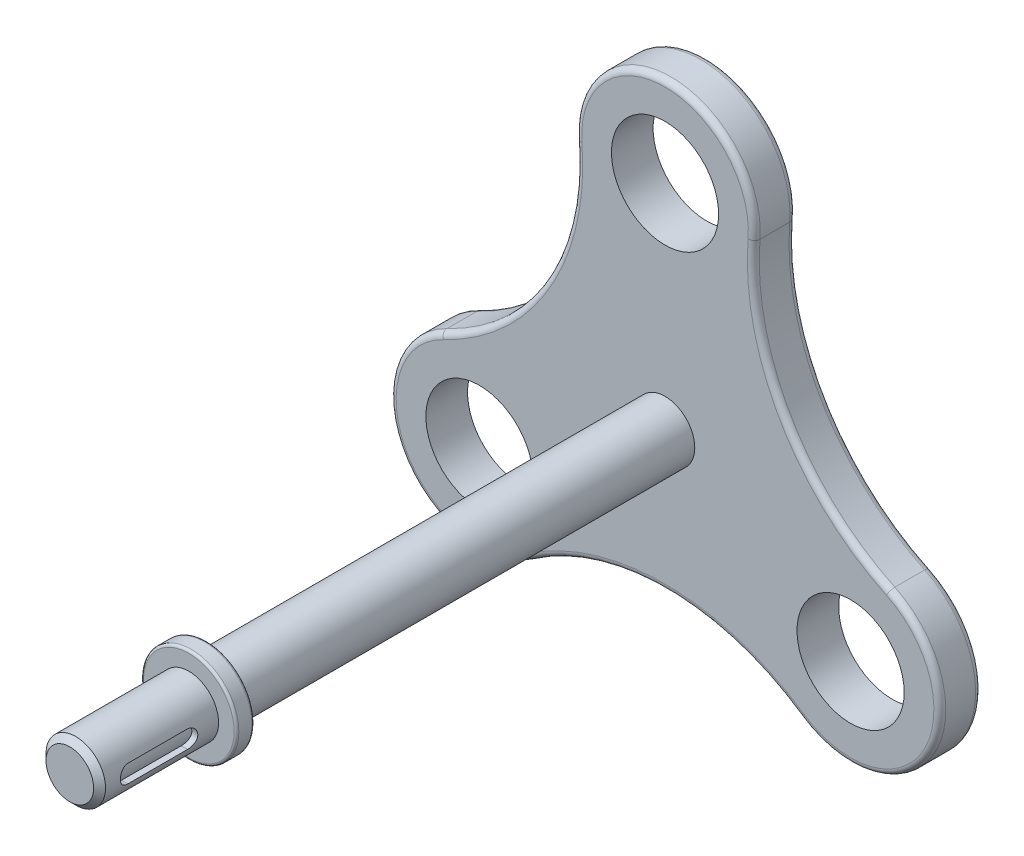
SolidWorks part; units mm, degrees
material "AISI 1020"
ref_plane "Front Plane" through (0, 0, 0) normal (0, 0, 1) x (1, 0, 0)
ref_plane "Top Plane" through (0, 0, 0) normal (0, 1, 0) x (1, 0, 0)
ref_plane "Right Plane" through (0, 0, 0) normal (1, 0, 0) x (0, 0, -1)
sketch "Sketch1" plane through (0, 0, 0) normal (0, 0, 1) x (1, 0, 0)
  arc A0 (7.4766, 17.4075) -> (-7.4766, 17.4075) centre (0, 18) ccw
  arc A1 (11.3371, -15.1786) -> (18.8136, -2.2289) centre (15.5885, -9) ccw
  arc A2 (-18.8136, -2.2289) -> (-11.3371, -15.1786) centre (-15.5885, -9) ccw
  arc A6 (-18.8136, -2.2289) -> (-7.4766, 17.4075) centre (-27.4141, 15.8275) ccw
  arc A7 (7.4766, 17.4075) -> (18.8136, -2.2289) centre (27.4141, 15.8275) ccw
  arc A8 (11.3371, -15.1786) -> (-11.3371, -15.1786) centre (0, -31.655) ccw
  circle A9 centre (0, 18) radius 4.5
  circle A10 centre (-15.5885, -9) radius 4.5
  circle A11 centre (15.5885, -9) radius 4.5
  point P9 (0, 0)
  point P20 (0, 0)
  dimension "D1" = 15
  dimension "D4" = 40
  dimension "D5" = 3
  dimension "D6" = 9
  dimension "D7" = 9
  dimension "D8" = 9
  dimension "D2" = 18
  dimension "D3" = 3
extrude "Boss-Extrude1" add sketch "Sketch1" along normal blind 3.5
sketch "Sketch2" plane through (0, 0, 3.5) normal (0, 0, 1) x (1, 0, 0)
  circle A0 centre (0, 0) radius 2.5
  dimension "D1" = 5
extrude "Boss-Extrude2" add sketch "Sketch2" along normal blind 50
chamfer "Chamfer1" distance 0.5 angle 45 1 edges at (2.5, 0, 53.5)
ref_plane "Plane1" through (0, 0, 43.5) normal (0, 0, 1) x (1, 0, 0)
sketch "Sketch4" plane through (0, 0, 43.5) normal (0, 0, 1) x (1, 0, 0)
  circle A0 centre (0, 0) radius 4
  dimension "D1" = 8
extrude "Boss-Extrude3" add sketch "Sketch4" against normal blind 1.5
fillet "Fillet1" radius 0.2 1 edges at (4, 0, 42)
sketch "Sketch5" plane through (0, 0, 0) normal (1, 0, 0) x (0, 0, -1)
  line L0 (-51, 0) -> (-46, 0) construction
  line L1 (-51, 0.75) -> (-46, 0.75)
  line L2 (-51, -0.75) -> (-46, -0.75)
  line L3 (-53.5, 2) -> (-53.5, -2) construction
  arc A0 (-51, 0.75) -> (-51, -0.75) centre (-51, 0) ccw
  arc A1 (-46, -0.75) -> (-46, 0.75) centre (-46, 0) ccw
  point P3 (-48.5, 0)
  dimension "D1" = 0.75
  dimension "D2" = 5
  dimension "D3" = 5
extrude "Cut-Extrude3" cut sketch "Sketch5" against normal offset from surface (3.146 mm away) 0.5 from offset 5 contours L1 A1 L2 A0
fillet "Fillet2" radius 0.2 1 edges at (4, 0, 43.5)
fillet "Fillet3" radius 0.5 12 edges at (10.0935, 5.8275, 3.5) (22.0836, -12.75, 3.5) (0, -11.655, 3.5) (-22.0836, -12.75, 3.5) (-10.0935, 5.8275, 3.5) (10.0935, 5.8275, 0) (22.0836, -12.75, 0) (0, -11.655, 0) (-22.0836, -12.75, 0) (-10.0935, 5.8275, 0) (0, 25.5, 3.5) (0, 25.5, 0)
